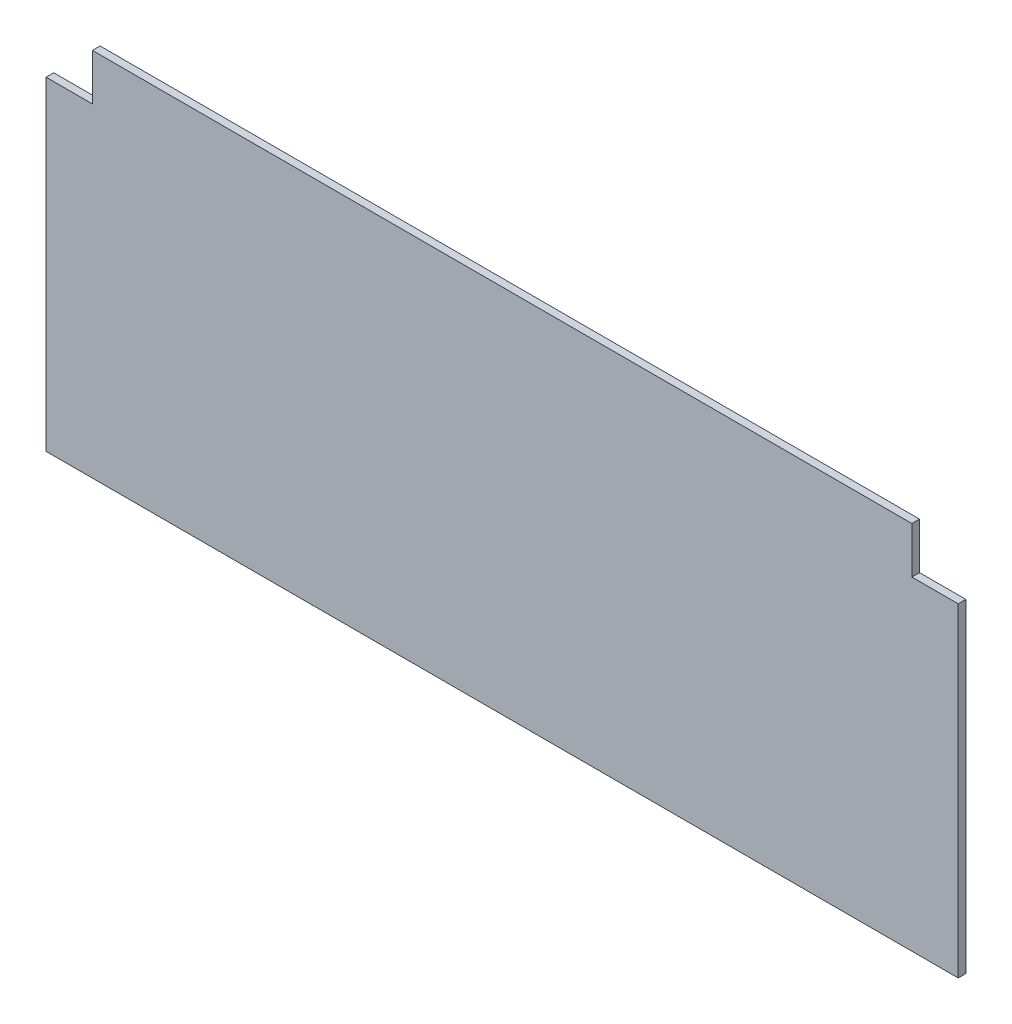
SolidWorks part; units mm, degrees
material "Balsa"
ref_plane "Front Plane" through (0, 0, 0) normal (0, 0, 1) x (1, 0, 0)
ref_plane "Top Plane" through (0, 0, 0) normal (0, 1, 0) x (1, 0, 0)
ref_plane "Right Plane" through (0, 0, 0) normal (1, 0, 0) x (0, 0, -1)
sketch "Sketch1" plane through (0, 0, 0) normal (0, 0, 1) x (1, 0, 0)
  line L0 (393.4, -179.5726) -> (393.4, -39.8043)
  line L1 (393.4, -39.8043) -> (0, -39.8043) construction
  line L2 (0, -39.8043) -> (0, -179.5726)
  line L3 (0, -179.5726) -> (393.4, -179.5726)
  line L4 (0, -138.3774) -> (0, -39.8043) construction
  line L5 (373.4, -39.8043) -> (20, -39.8043) construction
  line L6 (373.4, -39.8043) -> (373.4, -19.8043)
  line L7 (373.4, -19.8043) -> (20, -19.8043)
  line L8 (20, -39.8043) -> (20, -19.8043)
  line L9 (373.4, -39.8043) -> (20, -19.8043) construction
  line L10 (373.4, -19.8043) -> (20, -39.8043) construction
  line L11 (0, -179.5726) -> (393.4, -179.5726) construction
  line L13 (20.7, -19.8043) -> (372.7, -19.8043) construction
  line L14 (393.4, -39.8043) -> (393.4, -138.3812) construction
  line L19 (393.4, -39.8043) -> (373.4, -39.8043)
  line L20 (0, -39.8043) -> (20, -39.8043)
  point P12 (196.7, -29.8043)
  dimension "D1" = 20
  dimension "D2" = 20
  dimension "D3" = 20
extrude "Boss-Extrude1" add sketch "Sketch1" against normal blind 3.3 contours L2 L3 L0 L1 | L8 L1 L6 L7
